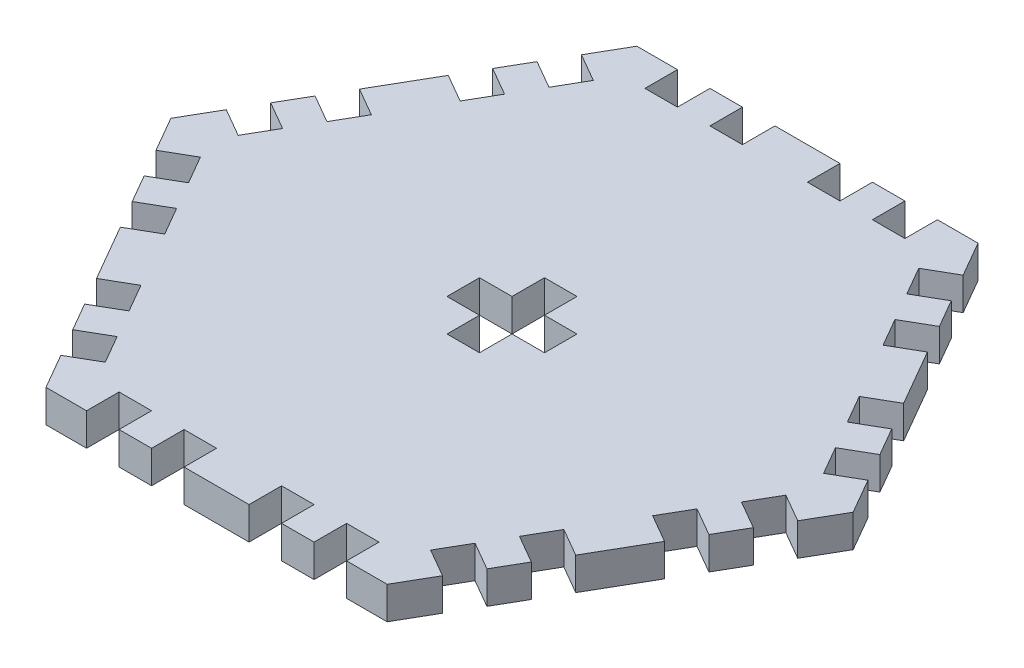
SolidWorks part; units mm, degrees
ref_plane "Front Plane" through (0, 0, 0) normal (0, 0, 1) x (1, 0, 0)
ref_plane "Top Plane" through (0, 0, 0) normal (0, 1, 0) x (1, 0, 0)
ref_plane "Right Plane" through (0, 0, 0) normal (1, 0, 0) x (0, 0, -1)
sketch "Sketch1" plane through (0, 0, 0) normal (0, 1, 0) x (1, 0, 0)
  line L1 (53.32, 0) -> (26.66, 46.1765)
  line L2 (26.66, 46.1765) -> (-26.66, 46.1765)
  line L3 (-26.66, 46.1765) -> (-53.32, 0)
  line L4 (-53.32, 0) -> (-26.66, -46.1765)
  line L5 (-26.66, -46.1765) -> (26.66, -46.1765)
  line L6 (26.66, -46.1765) -> (53.32, 0)
  circle A0 centre (0, 0) radius 46.1765 construction
  dimension "D1" = 53.32
extrude "Boss-Extrude1" add sketch "Sketch1" along normal blind 5.08
sketch "Sketch3" plane through (0, 5.08, 0) normal (0, 1, 0) x (1, 0, 0)
  line L0 (0, 46.1765) -> (0, -46.1765) construction
  line L1 (26.66, 46.1765) -> (-26.66, 46.1765) construction
  line L2 (-26.66, -46.1765) -> (26.66, -46.1765) construction
  line L3 (-53.32, 0) -> (53.32, 0) construction
  line L4 (-20.32, 46.1765) -> (-20.32, 41.0965)
  line L5 (5.08, 46.1765) -> (10.16, 46.1765)
  line L6 (5.08, 46.1765) -> (5.08, 41.0965)
  line L7 (5.08, 41.0965) -> (10.16, 41.0965)
  line L8 (10.16, 46.1765) -> (10.16, 41.0965)
  line L9 (15.24, 46.1765) -> (20.32, 46.1765)
  line L10 (15.24, 46.1765) -> (15.24, 41.0965)
  line L11 (15.24, 41.0965) -> (20.32, 41.0965)
  line L12 (20.32, 46.1765) -> (20.32, 41.0965)
  line L13 (-15.24, 41.0965) -> (-20.32, 41.0965)
  line L14 (-15.24, 46.1765) -> (-15.24, 41.0965)
  line L15 (-15.24, 46.1765) -> (-20.32, 46.1765)
  line L16 (-10.16, 46.1765) -> (-10.16, 41.0965)
  line L17 (-5.08, 41.0965) -> (-10.16, 41.0965)
  line L18 (-5.08, 46.1765) -> (-5.08, 41.0965)
  line L19 (-5.08, 46.1765) -> (-10.16, 46.1765)
  line L20 (29.83, 40.6859) -> (25.4306, 38.1459)
  line L21 (42.53, 18.6888) -> (45.07, 14.2894)
  line L22 (42.53, 18.6888) -> (38.1306, 16.1488)
  line L23 (38.1306, 16.1488) -> (40.6706, 11.7494)
  line L24 (45.07, 14.2894) -> (40.6706, 11.7494)
  line L25 (47.61, 9.89) -> (50.15, 5.4906)
  line L26 (47.61, 9.89) -> (43.2106, 7.35)
  line L27 (43.2106, 7.35) -> (45.7506, 2.9506)
  line L28 (50.15, 5.4906) -> (45.7506, 2.9506)
  line L29 (27.9706, 33.7465) -> (25.4306, 38.1459)
  line L30 (32.37, 36.2865) -> (27.9706, 33.7465)
  line L31 (32.37, 36.2865) -> (29.83, 40.6859)
  line L32 (34.91, 31.8871) -> (30.5106, 29.3471)
  line L33 (33.0506, 24.9476) -> (30.5106, 29.3471)
  line L34 (37.45, 27.4876) -> (33.0506, 24.9476)
  line L35 (37.45, 27.4876) -> (34.91, 31.8871)
  line L36 (50.15, -5.4906) -> (45.7506, -2.9506)
  line L37 (37.45, -27.4876) -> (34.91, -31.8871)
  line L38 (37.45, -27.4876) -> (33.0506, -24.9476)
  line L39 (33.0506, -24.9476) -> (30.5106, -29.3471)
  line L40 (34.91, -31.8871) -> (30.5106, -29.3471)
  line L41 (32.37, -36.2865) -> (29.83, -40.6859)
  line L42 (32.37, -36.2865) -> (27.9706, -33.7465)
  line L43 (27.9706, -33.7465) -> (25.4306, -38.1459)
  line L44 (29.83, -40.6859) -> (25.4306, -38.1459)
  line L45 (43.2106, -7.35) -> (45.7506, -2.9506)
  line L46 (47.61, -9.89) -> (43.2106, -7.35)
  line L47 (47.61, -9.89) -> (50.15, -5.4906)
  line L48 (45.07, -14.2894) -> (40.6706, -11.7494)
  line L49 (38.1306, -16.1488) -> (40.6706, -11.7494)
  line L50 (42.53, -18.6888) -> (38.1306, -16.1488)
  line L51 (42.53, -18.6888) -> (45.07, -14.2894)
  line L52 (20.32, -46.1765) -> (20.32, -41.0965)
  line L53 (-5.08, -46.1765) -> (-10.16, -46.1765)
  line L54 (-5.08, -46.1765) -> (-5.08, -41.0965)
  line L55 (-5.08, -41.0965) -> (-10.16, -41.0965)
  line L56 (-10.16, -46.1765) -> (-10.16, -41.0965)
  line L57 (-15.24, -46.1765) -> (-20.32, -46.1765)
  line L58 (-15.24, -46.1765) -> (-15.24, -41.0965)
  line L59 (-15.24, -41.0965) -> (-20.32, -41.0965)
  line L60 (-20.32, -46.1765) -> (-20.32, -41.0965)
  line L61 (15.24, -41.0965) -> (20.32, -41.0965)
  line L62 (15.24, -46.1765) -> (15.24, -41.0965)
  line L63 (15.24, -46.1765) -> (20.32, -46.1765)
  line L64 (10.16, -46.1765) -> (10.16, -41.0965)
  line L65 (5.08, -41.0965) -> (10.16, -41.0965)
  line L66 (5.08, -46.1765) -> (5.08, -41.0965)
  line L67 (5.08, -46.1765) -> (10.16, -46.1765)
  line L68 (-29.83, -40.6859) -> (-25.4306, -38.1459)
  line L69 (-42.53, -18.6888) -> (-45.07, -14.2894)
  line L70 (-42.53, -18.6888) -> (-38.1306, -16.1488)
  line L71 (-38.1306, -16.1488) -> (-40.6706, -11.7494)
  line L72 (-45.07, -14.2894) -> (-40.6706, -11.7494)
  line L73 (-47.61, -9.89) -> (-50.15, -5.4906)
  line L74 (-47.61, -9.89) -> (-43.2106, -7.35)
  line L75 (-43.2106, -7.35) -> (-45.7506, -2.9506)
  line L76 (-50.15, -5.4906) -> (-45.7506, -2.9506)
  line L77 (-27.9706, -33.7465) -> (-25.4306, -38.1459)
  line L78 (-32.37, -36.2865) -> (-27.9706, -33.7465)
  line L79 (-32.37, -36.2865) -> (-29.83, -40.6859)
  line L80 (-34.91, -31.8871) -> (-30.5106, -29.3471)
  line L81 (-33.0506, -24.9476) -> (-30.5106, -29.3471)
  line L82 (-37.45, -27.4876) -> (-33.0506, -24.9476)
  line L83 (-37.45, -27.4876) -> (-34.91, -31.8871)
  line L84 (-50.15, 5.4906) -> (-45.7506, 2.9506)
  line L85 (-37.45, 27.4876) -> (-34.91, 31.8871)
  line L86 (-37.45, 27.4876) -> (-33.0506, 24.9476)
  line L87 (-33.0506, 24.9476) -> (-30.5106, 29.3471)
  line L88 (-34.91, 31.8871) -> (-30.5106, 29.3471)
  line L89 (-32.37, 36.2865) -> (-29.83, 40.6859)
  line L90 (-32.37, 36.2865) -> (-27.9706, 33.7465)
  line L91 (-27.9706, 33.7465) -> (-25.4306, 38.1459)
  line L92 (-29.83, 40.6859) -> (-25.4306, 38.1459)
  line L93 (-43.2106, 7.35) -> (-45.7506, 2.9506)
  line L94 (-47.61, 9.89) -> (-43.2106, 7.35)
  line L95 (-47.61, 9.89) -> (-50.15, 5.4906)
  line L96 (-45.07, 14.2894) -> (-40.6706, 11.7494)
  line L97 (-38.1306, 16.1488) -> (-40.6706, 11.7494)
  line L98 (-42.53, 18.6888) -> (-38.1306, 16.1488)
  line L99 (-42.53, 18.6888) -> (-45.07, 14.2894)
  point P109 (0, 0)
  dimension "D1" = 5.08
  dimension "D2" = 5.08
  dimension "D3" = 5.08
  dimension "D4" = 5.08
  dimension "D5" = 5.08
  dimension "D6" = 5.08
  dimension "D7" = 6
extrude "Cut-Extrude1" cut sketch "Sketch3" against normal blind 5.08
sketch "Sketch4" plane through (0, 5.08, 0) normal (0, 1, 0) x (1, 0, 0)
  line L0 (0, 46.1765) -> (0, -46.1765) construction
  line L1 (5.08, 46.1765) -> (-5.08, 46.1765) construction
  line L2 (-5.08, -46.1765) -> (5.08, -46.1765) construction
  line L3 (-53.32, 0) -> (53.32, 0) construction
  line L4 (0, 7.62) -> (2.54, 7.62)
  line L5 (2.54, 7.62) -> (2.54, 2.54)
  line L6 (2.54, 2.54) -> (7.62, 2.54)
  line L7 (7.62, 2.54) -> (7.62, 0)
  line L8 (7.62, 0) -> (7.62, -2.54)
  line L9 (7.62, -2.54) -> (2.54, -2.54)
  line L10 (2.54, -2.54) -> (2.54, -7.62)
  line L11 (2.54, -7.62) -> (0, -7.62)
  line L12 (0, -7.62) -> (-2.54, -7.62)
  line L13 (-2.54, -7.62) -> (-2.54, -2.54)
  line L14 (-2.54, -2.54) -> (-7.62, -2.54)
  line L15 (-7.62, -2.54) -> (-7.62, 0)
  line L16 (-7.62, 0) -> (-7.62, 2.54)
  line L17 (-7.62, 2.54) -> (-2.54, 2.54)
  line L18 (-2.54, 2.54) -> (-2.54, 7.62)
  line L19 (-2.54, 7.62) -> (0, 7.62)
  point P33 (0, 0)
  dimension "D1" = 2.54
  dimension "D2" = 5.08
  dimension "D3" = 5.08
  dimension "D4" = 2.54
  dimension "D5" = 4
extrude "Cut-Extrude2" cut sketch "Sketch4" against normal blind 5.08
